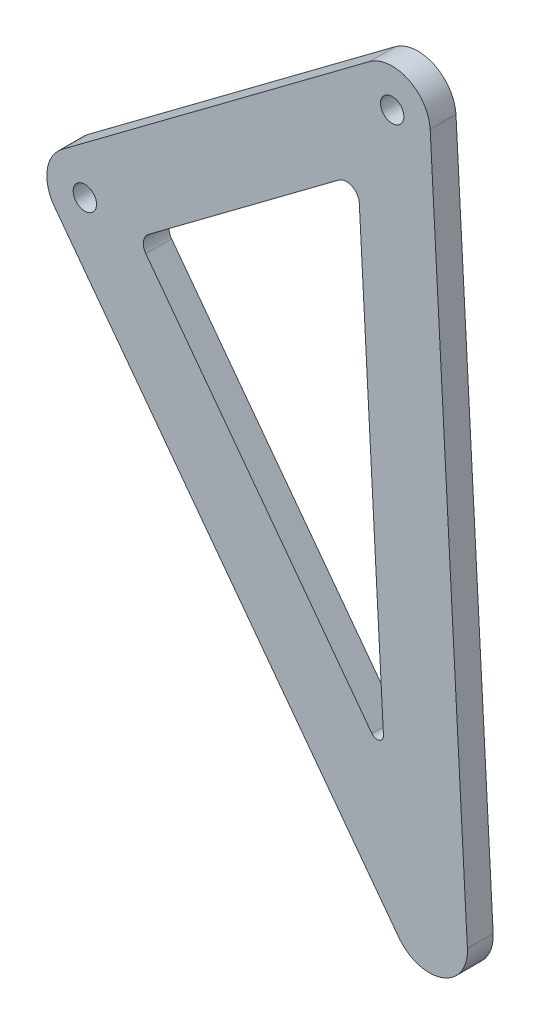
SolidWorks part; units mm, degrees
ref_plane "Front Plane" through (0, 0, 0) normal (0, 0, 1) x (1, 0, 0)
ref_plane "Top Plane" through (0, 0, 0) normal (0, 1, 0) x (1, 0, 0)
ref_plane "Right Plane" through (0, 0, 0) normal (1, 0, 0) x (0, 0, -1)
sketch "Sketch1" plane through (0, 0, 0) normal (0, 0, 1) x (1, 0, 0)
  line L7 (142.4123, 136.5177) -> (149.7424, 0.4252)
  line L26 (133.2063, 28.5418) -> (128.443, 116.9782)
  line L27 (86.3846, 87.3043) -> (130.9209, 27.7132)
  line L28 (136.2457, -4.4681) -> (68.359, 86.3667)
  line L29 (69.8768, 96.8642) -> (130.4333, 142.122)
  line L30 (124.3861, 118.8762) -> (86.8986, 90.8594)
  arc A73 (142.4123, 136.5177) -> (130.4333, 142.122) centre (134.9232, 136.1144) ccw
  arc A74 (142.6567, -7.4674) -> (149.7424, 0.4252) centre (142.2533, 0.0218) ccw
  arc A75 (136.2457, -4.4681) -> (142.6567, -7.4674) centre (142.2533, 0.0218) ccw
  arc A76 (69.8768, 96.8642) -> (68.359, 86.3667) centre (74.3666, 90.8566) ccw
  arc A77 (146.7432, -5.9858) -> (149.7424, 0.4252) centre (142.2533, 0.0218) ccw
  arc A78 (136.2457, -4.4681) -> (146.7432, -5.9858) centre (142.2533, 0.0218) ccw
  arc A79 (69.8768, 96.8642) -> (68.359, 86.3667) centre (74.3666, 90.8566) ccw
  arc A80 (140.9307, 140.6042) -> (130.4333, 142.122) centre (134.9232, 136.1144) ccw
  arc A81 (142.4123, 136.5177) -> (140.9307, 140.6042) centre (134.9232, 136.1144) ccw
  arc A82 (75.7435, 89.0143) -> (72.9897, 92.6989) centre (74.3666, 90.8566) ccw
  arc A83 (72.9897, 92.6989) -> (75.7435, 89.0143) centre (74.3666, 90.8566) ccw
  arc A86 (134.7995, 138.411) -> (135.0469, 133.8177) centre (134.9232, 136.1144) ccw
  arc A87 (135.0469, 133.8177) -> (134.7995, 138.411) centre (134.9232, 136.1144) ccw
  arc A88 (128.443, 116.9782) -> (124.3861, 118.8762) centre (125.9067, 116.8416) ccw
  arc A89 (86.8986, 90.8594) -> (86.3846, 87.3043) centre (88.4192, 88.8248) ccw
  arc A90 (133.2063, 28.5418) -> (130.9209, 27.7132) centre (131.9381, 28.4735) cw
  dimension "D1" = 2.54
  dimension "D2" = 1.27
extrude "Boss-Extrude1" add sketch "Sketch1" along normal blind 5.08
